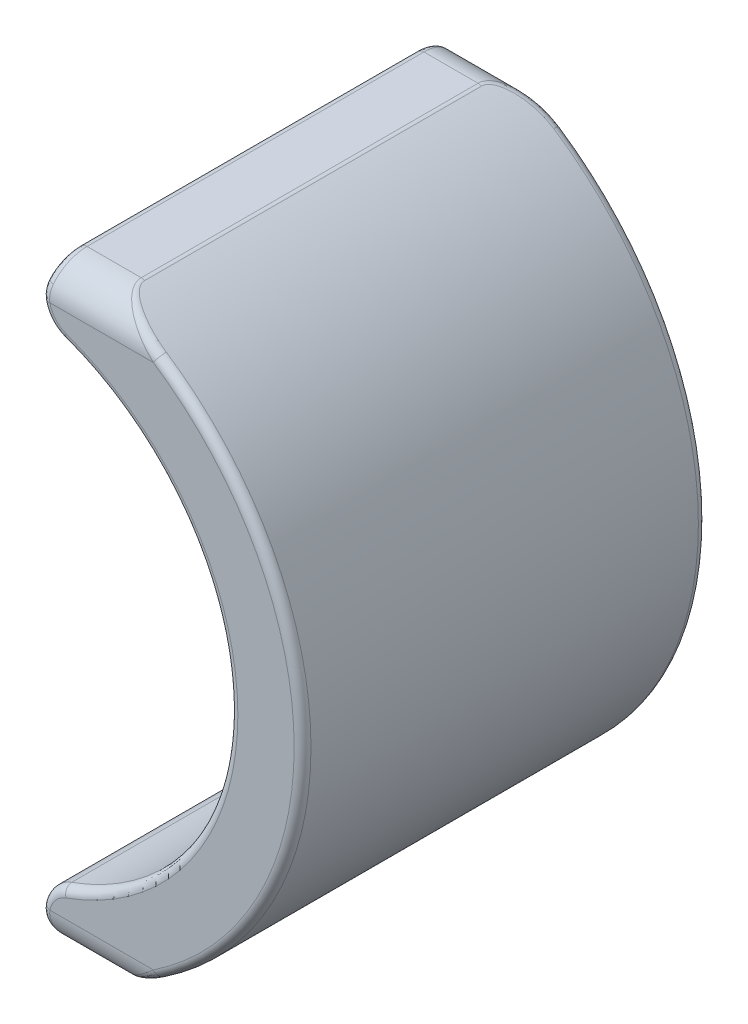
SolidWorks part; units mm, degrees
ref_plane "Front Plane" through (0, 0, 0) normal (0, 0, 1) x (1, 0, 0)
ref_plane "Top Plane" through (0, 0, 0) normal (0, 1, 0) x (1, 0, 0)
ref_plane "Right Plane" through (0, 0, 0) normal (1, 0, 0) x (0, 0, -1)
sketch "Sketch1" plane through (0, 0, 0) normal (0, 0, 1) x (1, 0, 0)
  line L0 (0, 0) -> (9.63, 0) construction
  line L1 (3.8934, -8.8078) -> (2.0334, -8.8078)
  line L2 (2.0334, -8.8078) -> (1.6779, -7.2678)
  line L3 (3.8934, 8.8078) -> (2.0334, 8.8078)
  line L4 (2.0334, 8.8078) -> (1.6779, 7.2678)
  arc A0 (3.8934, 8.8078) -> (3.8934, -8.8078) centre (0, 0) cw
  arc A1 (1.6779, 7.2678) -> (1.6779, -7.2678) centre (0, 0) cw
  point P9 (9.63, 0)
  dimension "D2" = 103
  dimension "D1" = 9.63
  dimension "D3" = 1.86
  dimension "D4" = 1.54
extrude "Boss-Extrude1" add sketch "Sketch1" along normal mid plane 12
fillet "Fillet1" radius 1 2 edges at (1.6779, -7.2678, 0) (1.6779, 7.2678, 0)
fillet "Fillet2" radius 1 4 edges at (2.9634, -8.8078, -6) (2.9634, -8.8078, 6) (2.9634, 8.8078, -6) (2.9634, 8.8078, 6)
fillet "Fillet3" radius 0.25 24 edges at (2.0919, 7.3238, -6) (1.864, 7.9472, -5.9902) (1.9941, 8.6375, -5.5583) (2.0334, 8.8078, 0) (1.9941, 8.6375, 5.5583) (1.8682, 8.0526, 5.9696) (2.0919, 7.3238, 6) (2.0919, -7.3238, 6) (1.864, -7.9472, 5.9902) (1.9941, -8.6375, 5.5583) (2.0334, -8.8078, 0) (1.9941, -8.6375, -5.5583) (1.8682, -8.0526, -5.9696) (2.0919, -7.3238, -6) (4.0741, -8.7257, 5.3968) (9.63, 0, 6) (4.0075, 8.7565, 5.3162) (3.8934, 8.8078, 0) (4.0741, 8.7257, -5.3968) (9.63, 0, -6) (4.0075, -8.7565, -5.3162) (3.8934, -8.8078, 0) (7.459, 0, 6) (7.459, 0, -6)
